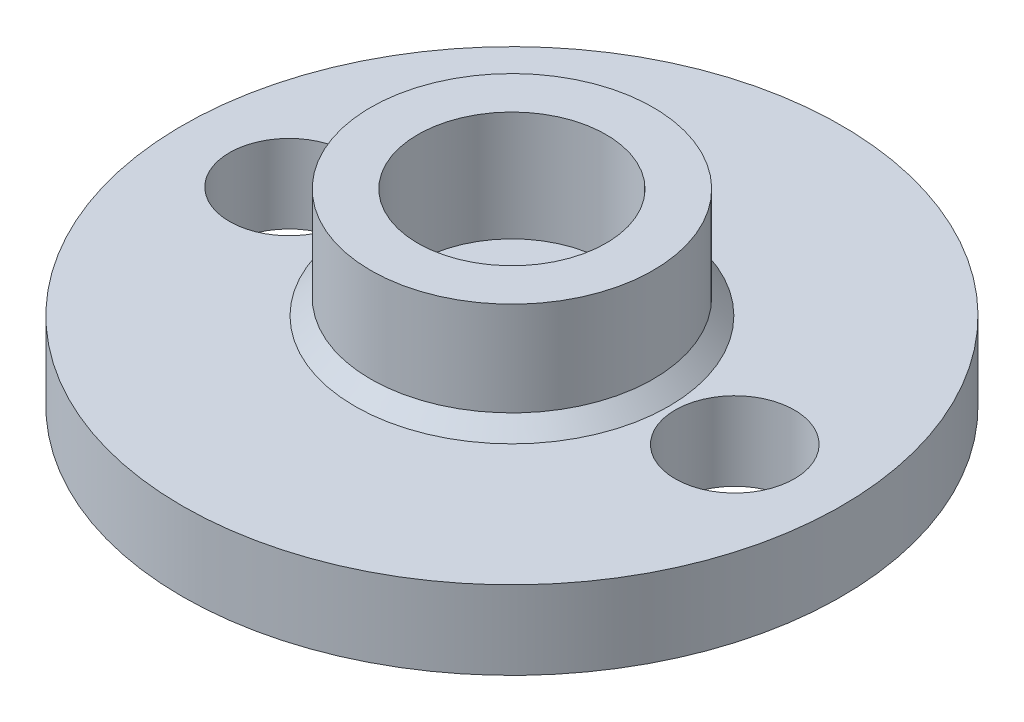
SolidWorks part; units mm, degrees
ref_plane "Front" through (0, 0, 0) normal (0, 0, 1) x (1, 0, 0)
ref_plane "Top" through (0, 0, 0) normal (0, 1, 0) x (1, 0, 0)
ref_plane "Right" through (0, 0, 0) normal (1, 0, 0) x (0, 0, -1)
sketch "Sketch1" plane through (0, 0, 0) normal (0, 1, 0) x (1, 0, 0)
  circle A0 centre (0, 0) radius 10.5
  dimension "D1" = 21
extrude "Boss-Extrude1" add sketch "Sketch1" along normal blind 2.5
sketch "Sketch2" plane through (0, 2.5, 0) normal (0, 1, 0) x (1, 0, 0)
  circle A0 centre (0, 0) radius 4.5
  circle A1 centre (0, 0) radius 3
  dimension "D1" = 9
  dimension "D2" = 6
extrude "Boss-Extrude2" add sketch "Sketch2" along normal blind 3.5
sketch "Sketch4" plane through (0, 2.5, 0) normal (0, 1, 0) x (1, 0, 0)
  circle A0 centre (0, 0) radius 1.5
  dimension "D1" = 3
extrude "Cut-Extrude1" cut sketch "Sketch4" against normal blind 3.5
sketch "Sketch5" plane through (0, 2.5, 0) normal (0, 1, 0) x (1, 0, 0)
  line L0 (0, 0) -> (0, 6.904) construction
  circle A0 centre (-7.1, 0) radius 1.9
  circle A1 centre (7.1, 0) radius 1.9
  dimension "D1" = 3.8
  dimension "D2" = 14.2
extrude "Cut-Extrude2" cut sketch "Sketch5" against normal through all both and the other way through all
chamfer "Chamfer1" distance 0.5 angle 45 1 edges at (0, 2.5, 4.5)
